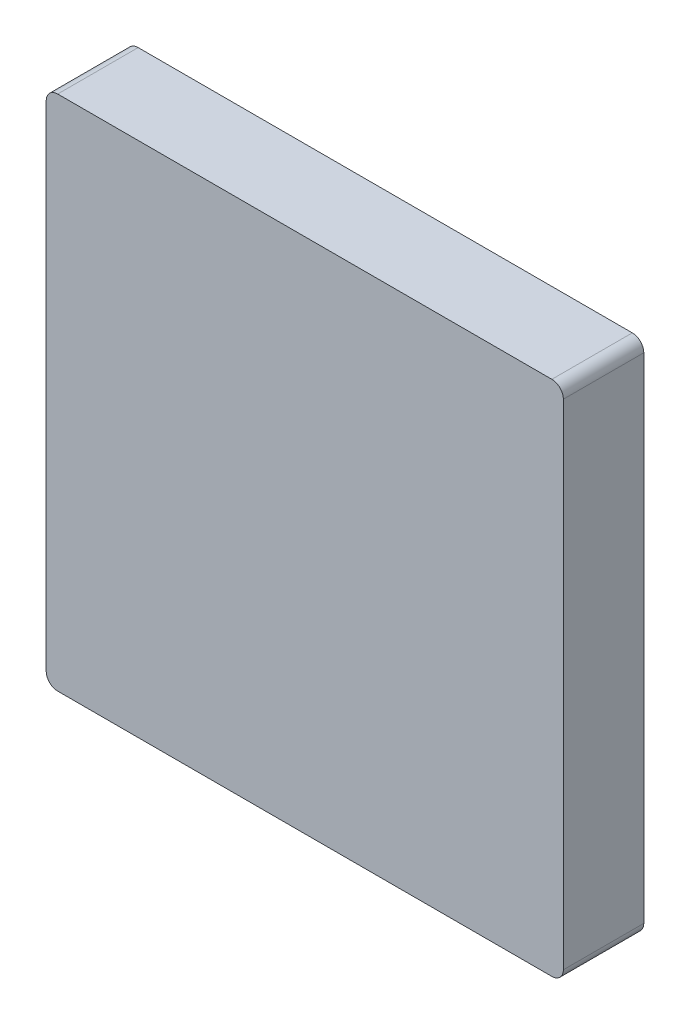
SolidWorks part; units mm, degrees
material "硅"
ref_plane "前视基准面" through (0, 0, 0) normal (0, 0, 1) x (1, 0, 0)
ref_plane "上视基准面" through (0, 0, 0) normal (0, 1, 0) x (1, 0, 0)
ref_plane "右视基准面" through (0, 0, 0) normal (1, 0, 0) x (0, 0, -1)
sketch "草图1" plane through (0, 0, 0) normal (0, 0, 1) x (1, 0, 0)
  line L1 (-6.3379, 7.5824) -> (-2.0379, 7.5824)
  line L2 (-6.4379, 7.4824) -> (-6.4379, 3.1824)
  line L3 (-6.3379, 3.0824) -> (-2.0379, 3.0824)
  line L4 (-1.9379, 7.4824) -> (-1.9379, 3.1824)
  arc A0 (-6.3379, 3.0824) -> (-6.4379, 3.1824) centre (-6.3379, 3.1824) cw
  arc A1 (-1.9379, 7.4824) -> (-2.0379, 7.5824) centre (-2.0379, 7.4824) ccw
  arc A2 (-1.9379, 3.1824) -> (-2.0379, 3.0824) centre (-2.0379, 3.1824) cw
  arc A3 (-6.3379, 7.5824) -> (-6.4379, 7.4824) centre (-6.3379, 7.4824) ccw
  point P6 (-6.4379, 3.0824)
  point P9 (-1.9379, 7.5824)
  point P14 (-6.4379, 7.5824)
  dimension "D3" = 0.1
  dimension "D1" = 4.5
  dimension "D2" = 4.5
extrude "凸台-拉伸1" add sketch "草图1" along normal blind 0.7
